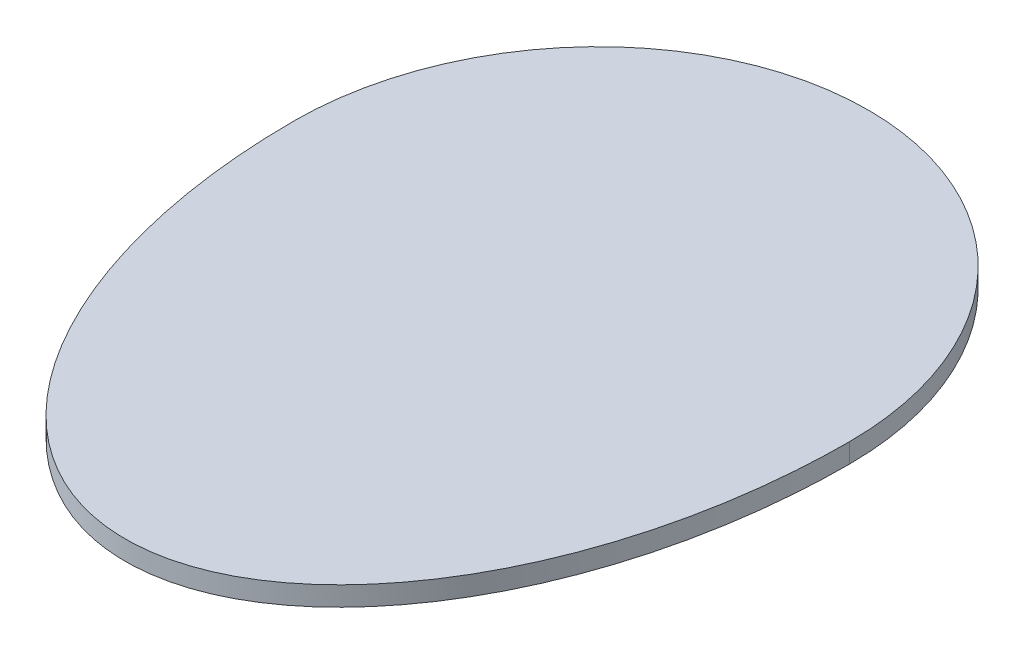
SolidWorks part; units mm, degrees
ref_plane "Front Plane" through (0, 0, 0) normal (0, 0, 1) x (1, 0, 0)
ref_plane "Top Plane" through (0, 0, 0) normal (0, 1, 0) x (1, 0, 0)
ref_plane "Right Plane" through (0, 0, 0) normal (1, 0, 0) x (0, 0, -1)
sketch "midlines" plane through (0, 0, 0) normal (0, 1, 0) x (1, 0, 0)
  line L0 (0, 0) -> (0, 106.76) construction
  line L1 (0, 0) -> (0, -160.73) construction
  line L2 (100, 0) -> (-100, 0) construction
  point P7 (0, 0)
  dimension "D1" = 106.76
  dimension "D2" = 160.73
  dimension "D3" = 200
sketch "Sketch4" plane through (0, 0, 0) normal (0, 1, 0) x (1, 0, 0)
  ellipse E0 centre (0, 0) end of major axis (0, 106.76) minor radius 100 (100, 0) -> (-100, 0) ccw
  ellipse E1 centre (0, 0) end of major axis (0, -160.73) minor radius 100 (100, 0) -> (-100, 0) cw
extrude "Boss-Extrude1" add sketch "Sketch4" along normal blind 7
